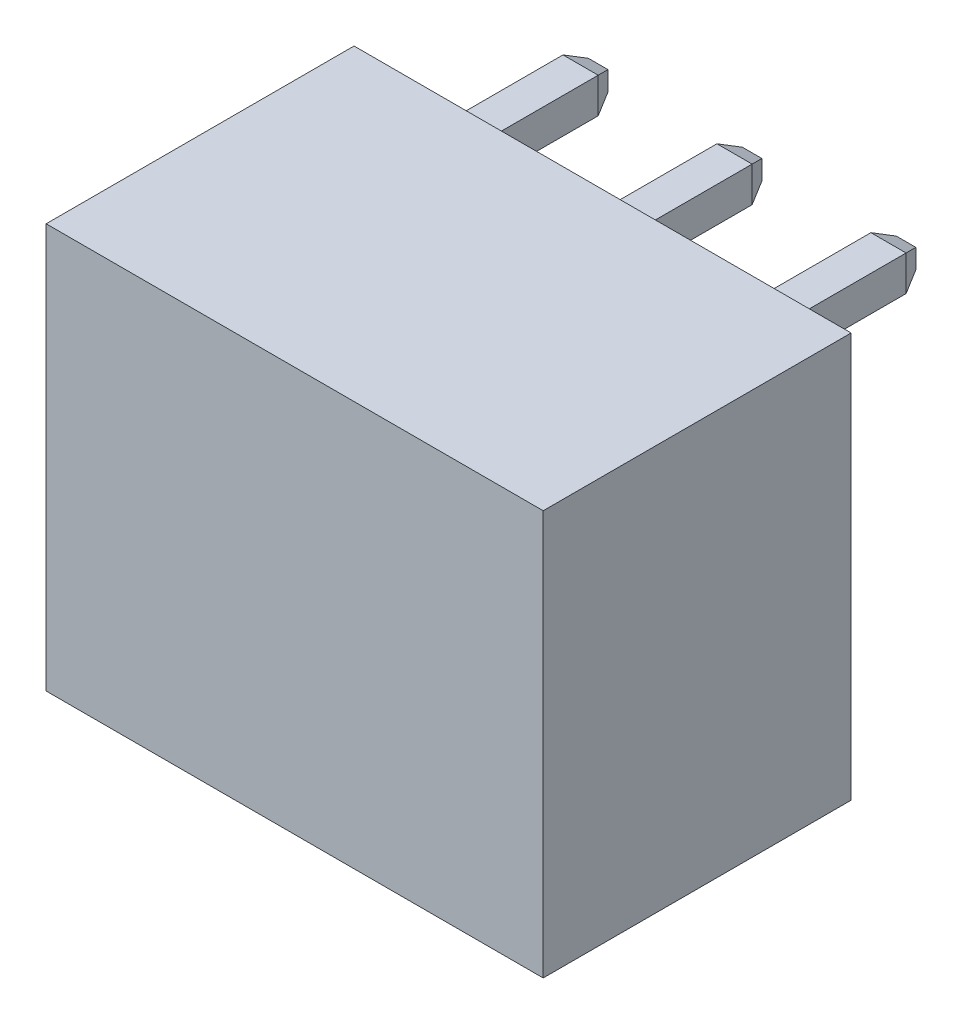
SolidWorks part; units mm, degrees
ref_plane "Спереди" through (0, 0, 0) normal (0, 0, 1) x (1, 0, 0)
ref_plane "Сверху" through (0, 0, 0) normal (0, 1, 0) x (1, 0, 0)
ref_plane "Справа" through (0, 0, 0) normal (1, 0, 0) x (0, 0, -1)
sketch "Эскиз1" plane through (0, 0, 0) normal (0, 0, 1) x (1, 0, 0)
  line L1 (5.65, 9.2) -> (-5.65, 9.2)
  line L2 (5.65, 9.2) -> (5.65, 0)
  line L3 (5.65, 0) -> (-5.65, 0)
  line L4 (-5.65, 9.2) -> (-5.65, 0)
  line L5 (5.65, 9.2) -> (-5.65, 0) construction
  line L6 (5.65, 0) -> (-5.65, 9.2) construction
  point P0 (0, 4.6)
  point P5 (0, 0)
  dimension "D1" = 9.2
  dimension "D2" = 11.3
extrude "Бобышка-Вытянуть1" add sketch "Эскиз1" along normal blind 7
sketch "Эскиз2" plane through (0, 0, 0) normal (0, 0, -1) x (-1, 0, 0)
  line L0 (5.65, 0) -> (-5.65, 0) construction
  line L1 (-3.9, 7.6) -> (-3.1, 7.6)
  line L2 (-3.9, 7.6) -> (-3.9, 8.4)
  line L3 (-3.9, 8.4) -> (-3.1, 8.4)
  line L4 (-3.1, 7.6) -> (-3.1, 8.4)
  line L5 (-3.9, 7.6) -> (-3.1, 8.4) construction
  line L6 (-3.9, 8.4) -> (-3.1, 7.6) construction
  line L7 (-5.65, 0) -> (-5.65, 9.2) construction
  point P0 (-3.5, 8)
  dimension "D1" = 8
  dimension "D2" = 0.8
  dimension "D3" = 2.15
extrude "Бобышка-Вытянуть2" add sketch "Эскиз2" along normal blind 3.4
chamfer "Фаска1" distance 0.4 angle 24 4 edges at (3.5, 8.4, -3.4) (3.1, 8, -3.4) (3.5, 7.6, -3.4) (3.9, 8, -3.4)
sketch "Эскиз3" plane through (0, 0, 0) normal (0, -1, 0) x (1, 0, 0)
  line L1 (1.9, 0.8) -> (5, 0.8)
  line L2 (1.9, 0.8) -> (1.9, 5)
  line L4 (5, 0.8) -> (5, 5)
  line L5 (1.9, 0.8) -> (5, 5) construction
  line L6 (1.9, 5) -> (5, 0.8) construction
  line L7 (-5.65, 0) -> (5.65, 0) construction
  line L9 (5.65, 7) -> (5.65, 0) construction
  line L10 (-5.65, 7) -> (5.65, 7) construction
  line L11 (1.9, 6.5) -> (5, 6.5)
  line L12 (1.9, 5) -> (2.9, 5)
  line L13 (2.9, 5) -> (1.9, 6.5)
  line L14 (5, 5) -> (4, 5)
  line L15 (4, 5) -> (5, 6.5)
  point P0 (3.45, 2.9)
  point P5 (3.45, 6.5)
  dimension "D1" = 2.2
  dimension "D2" = 0.8
  dimension "D3" = 2
  dimension "D4" = 3.1
  dimension "D5" = 0.5
  dimension "D6" = 1
extrude "Вырез-Вытянуть1" cut sketch "Эскиз3" against normal blind 7
pattern_linear "Линейный массив1" count 3 spacing 3.5 along (-1, 0, 0) of "Бобышка-Вытянуть2", "Фаска1"
pattern_linear "Линейный массив2" count 3 spacing 3.5 along (-1, 0, 0) of "Вырез-Вытянуть1"
sketch "Эскиз4" plane through (0, 7, 0) normal (0, -1, 0) x (1, 0, 0)
  line L0 (3.9, -3) -> (3.9, 0) construction
  line L1 (3.1, 3.4) -> (3.9, 3.4)
  line L2 (3.1, 3.4) -> (3.1, 2.6)
  line L3 (3.1, 2.6) -> (3.9, 2.6)
  line L4 (3.9, 3.4) -> (3.9, 2.6)
  line L5 (3.1, 3.4) -> (3.9, 2.6) construction
  line L6 (3.1, 2.6) -> (3.9, 3.4) construction
  line L7 (3.1, -3) -> (3.1, 0) construction
  line L8 (-5.65, 0) -> (5.65, 0) construction
  point P0 (3.5, 3)
  point P5 (0, 0)
  dimension "D1" = 3
extrude "Бобышка-Вытянуть3" add sketch "Эскиз4" along normal blind 6
chamfer "Фаска2" distance 0.4 angle 24 4 edges at (3.9, 1, 3) (3.5, 1, 3.4) (3.1, 1, 3) (3.5, 1, 2.6)
pattern_linear "Линейный массив3" count 3 spacing 3.5 along (-1, 0, 0) of "Фаска2", "Бобышка-Вытянуть3"
equation "\"n\" = 3"
equation "\"width\" = 3.5 * ( \"n\" - 1 ) + 4.3"
equation "\"D2@Эскиз1\" = 3.5 * ( \"n\" - 1 ) + 4.3"
